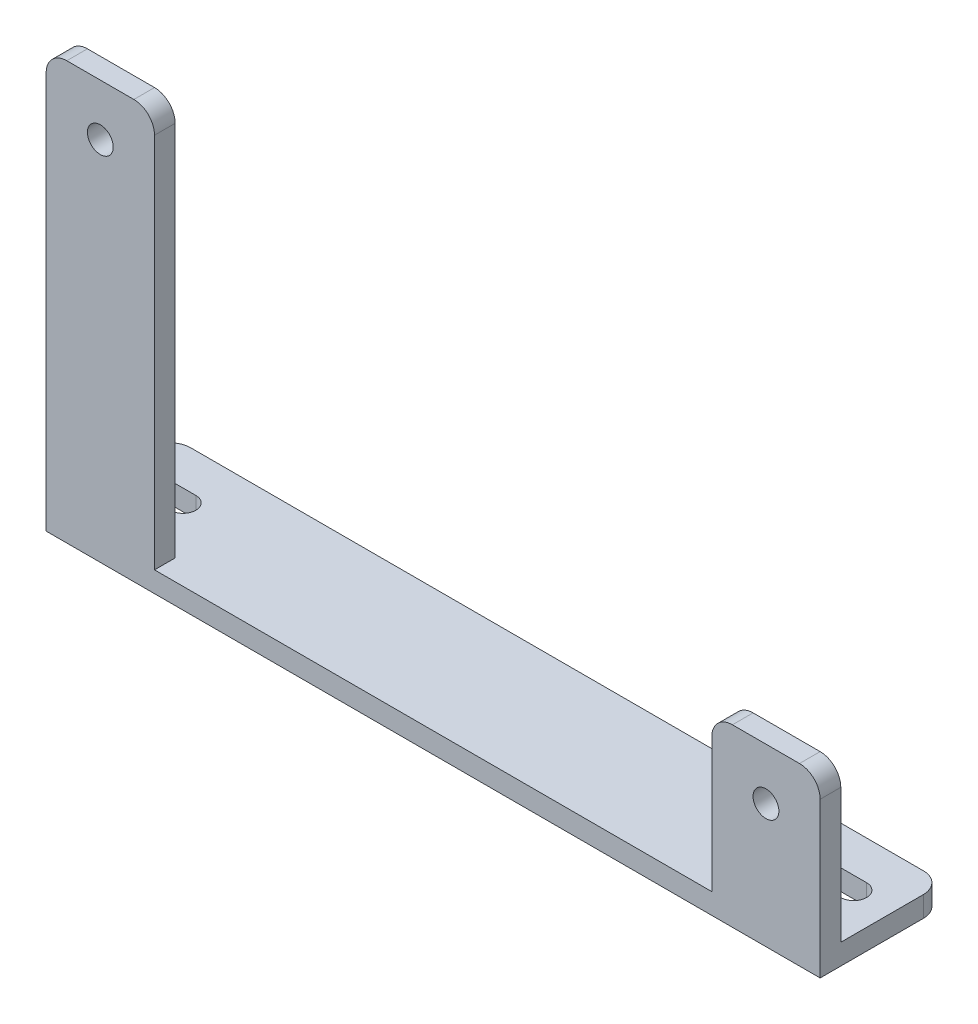
SolidWorks part; units mm, degrees
ref_plane "Front Plane" through (0, 0, 0) normal (0, 0, 1) x (1, 0, 0)
ref_plane "Top Plane" through (0, 0, 0) normal (0, 1, 0) x (1, 0, 0)
ref_plane "Right Plane" through (0, 0, 0) normal (1, 0, 0) x (0, 0, -1)
sketch "Sketch1" plane through (0, 0, 0) normal (0, 1, 0) x (1, 0, 0)
  line L0 (-67.5, 0) -> (-62.5, 0) construction
  line L1 (-75, 10) -> (75, 10)
  line L2 (-75, 10) -> (-75, -10)
  line L3 (-75, -10) -> (75, -10)
  line L4 (75, 10) -> (75, -10)
  line L5 (-75, 10) -> (75, -10) construction
  line L6 (-75, -10) -> (75, 10) construction
  line L7 (-67.5, 2.5) -> (-62.5, 2.5)
  line L8 (-67.5, -2.5) -> (-62.5, -2.5)
  line L9 (62.5, 0) -> (67.5, 0) construction
  line L10 (62.5, 2.5) -> (67.5, 2.5)
  line L11 (62.5, -2.5) -> (67.5, -2.5)
  arc A0 (-67.5, 2.5) -> (-67.5, -2.5) centre (-67.5, 0) ccw
  arc A1 (-62.5, -2.5) -> (-62.5, 2.5) centre (-62.5, 0) ccw
  arc A2 (62.5, 2.5) -> (62.5, -2.5) centre (62.5, 0) ccw
  arc A3 (67.5, -2.5) -> (67.5, 2.5) centre (67.5, 0) ccw
  point P0 (0, 0)
  point P8 (-65, 0)
  point P13 (65, 0)
  point P20 (0, 0)
  point P22 (-42.9327, 12.2021)
  dimension "D3" = 2.5
  dimension "D4" = 2.5
  dimension "D1" = 150
  dimension "D2" = 20
  dimension "D5" = 5
  dimension "D6" = 5
  dimension "D7" = 130
  dimension "D8" = 65
extrude "Boss-Extrude1" add sketch "Sketch1" along normal blind 4
sketch "Sketch2" plane through (0, 0, 10) normal (0, 0, 1) x (1, 0, 0)
  line L0 (-75, 4) -> (75, 4) construction
  line L1 (-75, 0) -> (-54, 0)
  line L2 (-75, 0) -> (-75, 80.9522)
  line L3 (-75, 80.9522) -> (-54, 80.9522)
  line L4 (-54, 0) -> (-54, 80.9522)
  line L5 (75, 0) -> (54, 0)
  line L6 (75, 0) -> (75, 34)
  line L7 (75, 34) -> (54, 34)
  line L8 (54, 0) -> (54, 34)
  line L9 (64.5, 24) -> (-64.5, 24) construction
  line L10 (-64.5, 24) -> (-64.5, 70.9522) construction
  line L11 (64.5, 24) -> (-64.5, 70.9522) construction
  line L12 (-75, 4) -> (75, 4)
  line L13 (75, 4) -> (75, 0)
  line L14 (-75, 0) -> (-75, 4)
  circle A0 centre (-64.5, 70.9522) radius 2.5
  circle A1 centre (64.5, 24) radius 2.5
  line M17 (-75, 0) -> (75, 0)
  line M18 (75, 0) -> (75, 4)
  line M19 (75, 4) -> (-75, 4)
  line M20 (-75, 4) -> (-75, 0)
  dimension "D7" = 20
  dimension "D9" = 76.9522
  dimension "D10" = 5
  dimension "D11" = 5
  dimension "D1" = 21
  dimension "D2" = 20
  dimension "D3" = 10.5
  dimension "D4" = 21
  dimension "D5" = 10.5
  dimension "D6" = 10
  dimension "D8" = 10
extrude "Boss-Extrude2" add sketch "Sketch2" along normal blind 4 contours L4 L3 L2 A0 M19 | L4 M17 M19 M20 | L8 L4 M17 M19 | L8 M17 M18 M19 | L8 L6 L7 A1 M19
fillet "Fillet1" radius 4 6 edges at (-54, 80.9522, 12) (-75, 80.9522, 12) (-75, 2, -10) (54, 34, 12) (75, 34, 12) (75, 2, -10)
